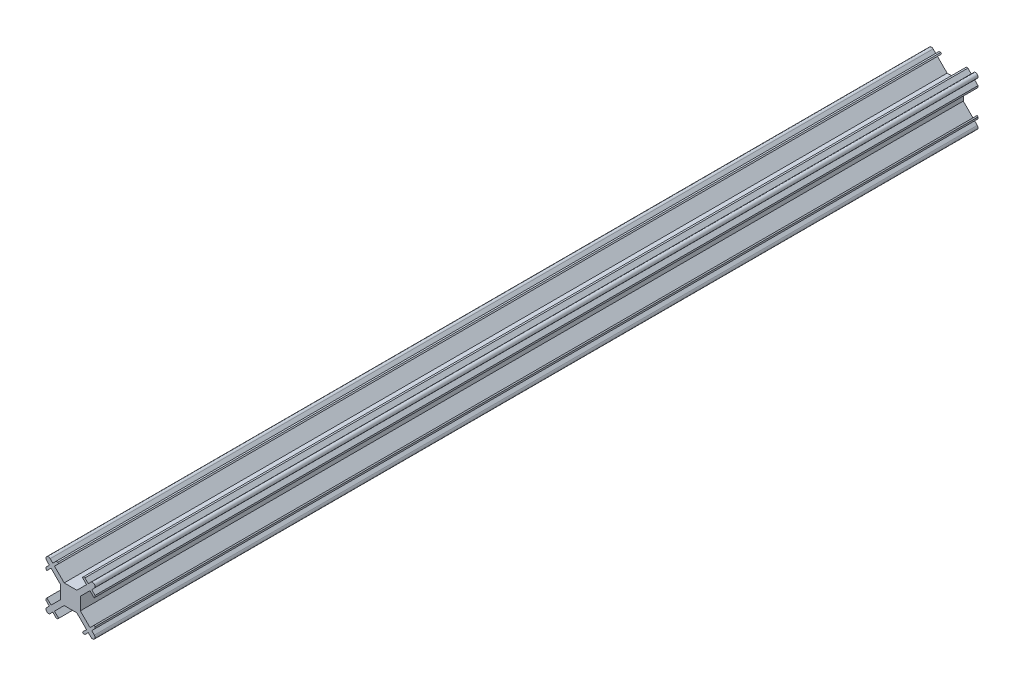
SolidWorks part; units mm, degrees
material "6061 Alloy"
ref_plane "Front Plane" through (0, 0, 0) normal (0, 0, 1) x (1, 0, 0)
ref_plane "Top Plane" through (0, 0, 0) normal (0, 1, 0) x (1, 0, 0)
ref_plane "Right Plane" through (0, 0, 0) normal (1, 0, 0) x (0, 0, -1)
sketch "Sketch1" plane through (0, 0, 0) normal (0, 0, 1) x (1, 0, 0)
  line L0 (-5, -5) -> (5, 5) construction
  line L1 (-5, 5) -> (5, 5)
  line L2 (-5, 5) -> (-5, -5)
  line L3 (-5, -5) -> (5, -5)
  line L4 (5, 5) -> (5, -5)
  line L5 (-2, 2) -> (2, -2) construction
  line L6 (-2, 2) -> (2, 2)
  line L7 (-2, 2) -> (-2, -2)
  line L8 (-2, -2) -> (2, -2)
  line L9 (2, 2) -> (2, -2)
  dimension "D1" = 10
  dimension "D2" = 4
sketch "Sketch2" plane through (0, 0, 0) normal (0, 0, 1) x (1, 0, 0)
  line L0 (-4.8536, 4.1464) -> (-4.3232, 3.6161)
  line L1 (-4.1464, 4.8536) -> (-3.6161, 4.3232)
  line L2 (-4.5, 4.5) -> (-2, 2) construction
  line L3 (-5, 5) -> (5, 5) construction
  line L4 (-5, 5) -> (-5, -5) construction
  line L5 (-2.9393, 5) -> (-3.6161, 4.3232)
  line L6 (-5, 2.5958) -> (-4.8182, 2.414)
  line L7 (-4.8182, 2.414) -> (-3.9697, 3.2626)
  line L8 (-2.414, 4.8182) -> (-2.5958, 5)
  line L9 (-4.3232, 3.6161) -> (-5, 2.9393)
  line L10 (-3.2626, 3.9697) -> (-2.414, 4.8182)
  line L11 (-3.2626, 3.9697) -> (-1.2929, 2)
  line L12 (-3.9697, 3.2626) -> (-2, 1.2929)
  line L14 (-5, 2.9393) -> (-5, 2.5958)
  line L15 (-2.9393, 5) -> (-2.5958, 5)
  line L16 (-2, 2) -> (-2, -2) construction
  line L17 (-2, -2) -> (2, -2) construction
  line L18 (2, 2) -> (2, -2) construction
  line L19 (-2, 2) -> (2, 2) construction
  line L20 (-2, 1.2929) -> (-2, -1.2929)
  line L21 (-1.2929, -2) -> (1.2929, -2)
  line L22 (2, 1.2929) -> (2, -1.2929)
  line L23 (-1.2929, 2) -> (1.2929, 2)
  line L24 (4.1464, 4.8536) -> (3.6161, 4.3232)
  line L25 (4.8536, 4.1464) -> (4.3232, 3.6161)
  line L26 (5, 2.9393) -> (4.3232, 3.6161)
  line L27 (2.5958, 5) -> (2.414, 4.8182)
  line L28 (2.414, 4.8182) -> (3.2626, 3.9697)
  line L29 (4.8182, 2.414) -> (5, 2.5958)
  line L30 (3.6161, 4.3232) -> (2.9393, 5)
  line L31 (3.9697, 3.2626) -> (4.8182, 2.414)
  line L32 (3.9697, 3.2626) -> (2, 1.2929)
  line L33 (3.2626, 3.9697) -> (1.2929, 2)
  line L34 (2.9393, 5) -> (2.5958, 5)
  line L35 (5, 2.9393) -> (5, 2.5958)
  line L36 (4.8536, -4.1464) -> (4.3232, -3.6161)
  line L37 (4.1464, -4.8536) -> (3.6161, -4.3232)
  line L38 (2.9393, -5) -> (3.6161, -4.3232)
  line L39 (5, -2.5958) -> (4.8182, -2.414)
  line L40 (4.8182, -2.414) -> (3.9697, -3.2626)
  line L41 (2.414, -4.8182) -> (2.5958, -5)
  line L42 (4.3232, -3.6161) -> (5, -2.9393)
  line L43 (3.2626, -3.9697) -> (2.414, -4.8182)
  line L44 (3.2626, -3.9697) -> (1.2929, -2)
  line L45 (3.9697, -3.2626) -> (2, -1.2929)
  line L46 (5, -2.9393) -> (5, -2.5958)
  line L47 (2.9393, -5) -> (2.5958, -5)
  line L48 (-4.1464, -4.8536) -> (-3.6161, -4.3232)
  line L49 (-4.8536, -4.1464) -> (-4.3232, -3.6161)
  line L50 (-5, -2.9393) -> (-4.3232, -3.6161)
  line L51 (-2.5958, -5) -> (-2.414, -4.8182)
  line L52 (-2.414, -4.8182) -> (-3.2626, -3.9697)
  line L53 (-4.8182, -2.414) -> (-5, -2.5958)
  line L54 (-3.6161, -4.3232) -> (-2.9393, -5)
  line L55 (-3.9697, -3.2626) -> (-4.8182, -2.414)
  line L56 (-3.9697, -3.2626) -> (-2, -1.2929)
  line L57 (-3.2626, -3.9697) -> (-1.2929, -2)
  line L58 (-2.9393, -5) -> (-2.5958, -5)
  line L59 (-5, -2.9393) -> (-5, -2.5958)
  arc A0 (-4.8536, 4.1464) -> (-4.1464, 4.8536) centre (-4.5, 4.5) cw
  arc A1 (4.1464, 4.8536) -> (4.8536, 4.1464) centre (4.5, 4.5) cw
  arc A2 (4.8536, -4.1464) -> (4.1464, -4.8536) centre (4.5, -4.5) cw
  arc A3 (-4.1464, -4.8536) -> (-4.8536, -4.1464) centre (-4.5, -4.5) cw
  point P74 (0, 0)
  dimension "D3" = 1.25
  dimension "D1" = 1
  dimension "D2" = 3.4
  dimension "D4" = 0.5
  dimension "D5" = 4
extrude "Boss-Extrude1" add sketch "Sketch2" along normal mid plane 180
